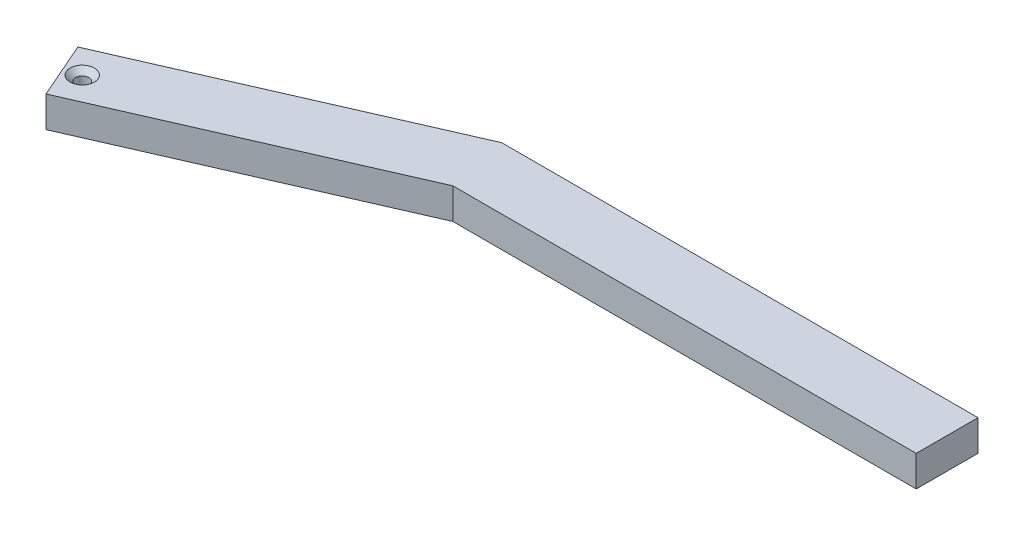
SolidWorks part; units mm, degrees
ref_plane "Front Plane" through (0, 0, 0) normal (0, 0, 1) x (1, 0, 0)
ref_plane "Top Plane" through (0, 0, 0) normal (0, 1, 0) x (1, 0, 0)
ref_plane "Right Plane" through (0, 0, 0) normal (1, 0, 0) x (0, 0, -1)
sketch "Sketch1" plane through (0, 0, 0) normal (0, 1, 0) x (1, 0, 0)
  line L0 (0, 0) -> (242.4215, 106.1223)
  line L1 (242.4215, 106.1223) -> (634.0535, 106.1223)
  line L2 (634.0535, 106.1223) -> (634.0535, 55.3223)
  line L3 (634.0535, 55.3223) -> (253.0535, 55.3223)
  line L4 (253.0535, 55.3223) -> (20.3717, -46.5364)
  line L5 (20.3717, -46.5364) -> (0, 0)
  dimension "D1" = 381
  dimension "D2" = 254
  dimension "D3" = 50.8
  dimension "D4" = 50.8
extrude "Boss-Extrude1" add sketch "Sketch1" along normal blind 25.4
hole_wizard "CSK for M10 Flat Head Machine Screw1" positions "Sketch4" profile "Sketch5" countersink size "M10" standard "ANSI Metric" end condition through all
sketch "Sketch4" plane through (0, 25.4, 0) normal (0, 1, 0) x (1, 0, 0)
  line L0 (10.1859, -23.2682) -> (53.5308, -4.2935) construction
  line L1 (0, 0) -> (20.3717, -46.5364) construction
  point P0 (21.82, -18.1752)
  dimension "D1" = 12.7
sketch "Sketch5" plane through (21.82, 25.4, 18.1752) normal (1, 0, 0) x (0, 0, 1)
  line L0 (0, 0) -> (0, 25.4)
  line L1 (0, 25.4) -> (5.5, 25.4)
  line L2 (5.5, 25.4) -> (5.5, 4.5)
  line L3 (5.5, 4.5) -> (10, 0)
  line L5 (10, 0) -> (0, 0)
  line L6 (-5.5, 4.5) -> (-10, 0) construction
  line L11 (0, -6.35) -> (0, 107.95) construction
  dimension "Thru Hole Dia." = 11
  dimension "Thru Hole Depth" = 25.4
  dimension "Near C'Sink Dia." = 20
  dimension "Near C'Sink Angle" = 90
